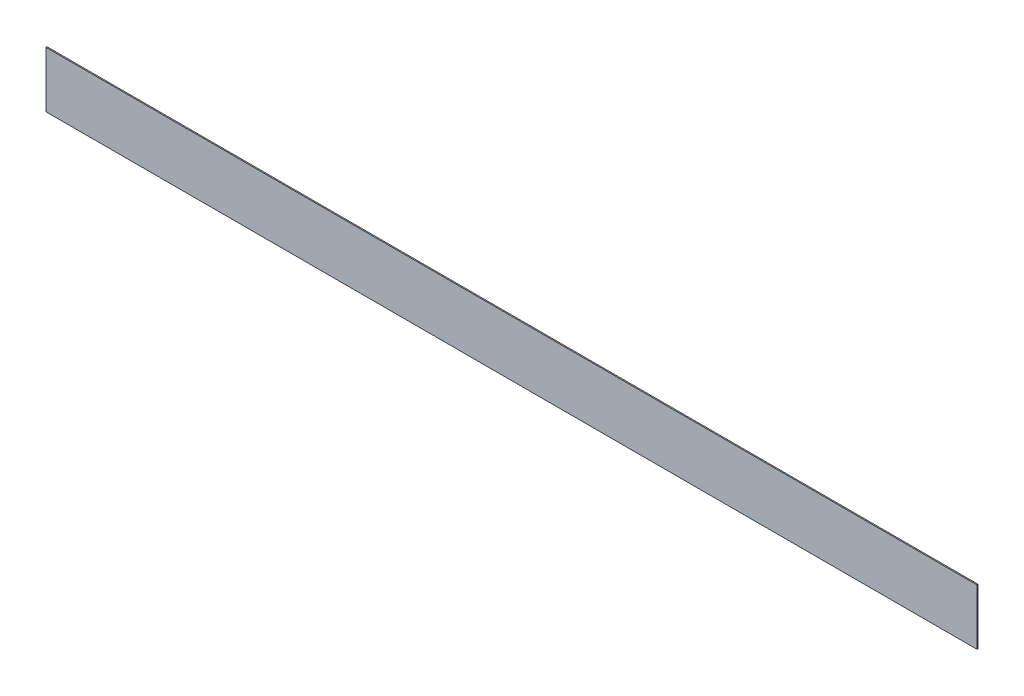
SolidWorks part; units mm, degrees
ref_plane "Front Plane" through (0, 0, 0) normal (0, 0, 1) x (1, 0, 0)
ref_plane "Top Plane" through (0, 0, 0) normal (0, 1, 0) x (1, 0, 0)
ref_plane "Right Plane" through (0, 0, 0) normal (1, 0, 0) x (0, 0, -1)
other "Configuration Table"
sketch "Sketch1" plane through (0, 0, 0) normal (0, 0, 1) x (1, 0, 0)
  line L1 (66, 690) -> (1334, 690)
  line L2 (66, 690) -> (66, 766)
  line L3 (66, 766) -> (1334, 766)
  line L4 (1334, 690) -> (1334, 766)
extrude "STORE_panel_ayirici_on_1" add sketch "Sketch1" along normal blind 1.5 from offset 38.5 separate body
